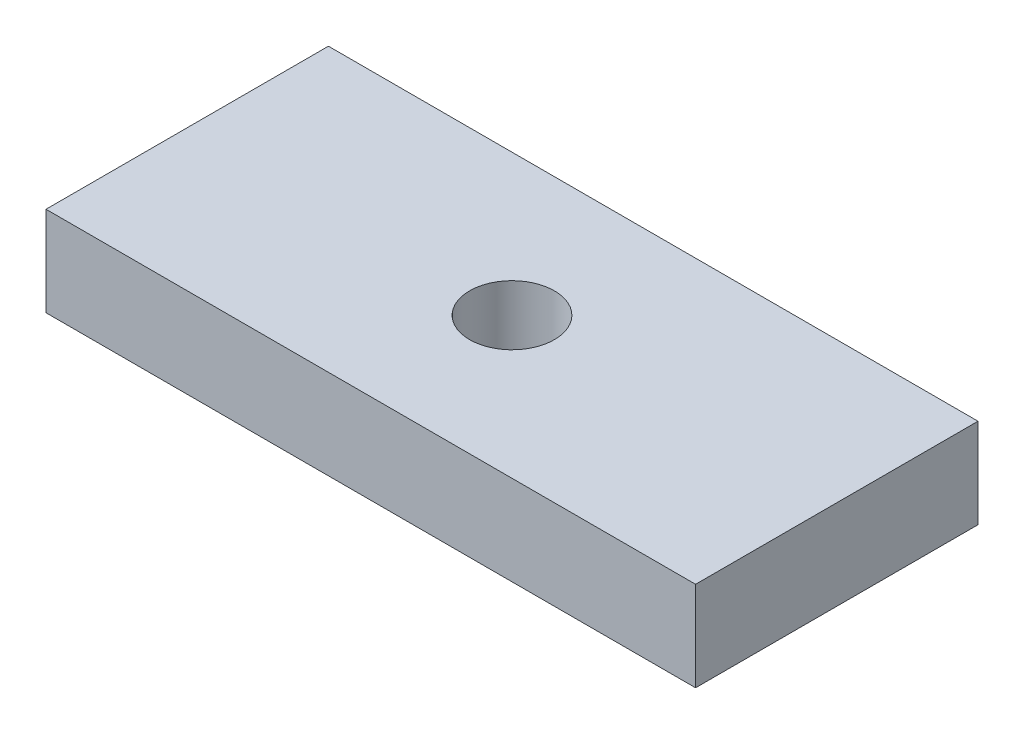
SolidWorks part; units mm, degrees
ref_plane "Front Plane" through (0, 0, 0) normal (0, 0, 1) x (1, 0, 0)
ref_plane "Top Plane" through (0, 0, 0) normal (0, 1, 0) x (1, 0, 0)
ref_plane "Right Plane" through (0, 0, 0) normal (1, 0, 0) x (0, 0, -1)
sketch "Sketch1" plane through (0, 0, 0) normal (0, 1, 0) x (1, 0, 0)
  line L1 (-23, 10) -> (23, 10)
  line L2 (-23, 10) -> (-23, -10)
  line L3 (-23, -10) -> (23, -10)
  line L4 (23, 10) -> (23, -10)
  line L5 (-23, 10) -> (23, -10) construction
  line L6 (-23, -10) -> (23, 10) construction
  circle A0 centre (0, 0) radius 3
  dimension "D1" = 6
  dimension "D2" = 20
  dimension "D3" = 46
extrude "Boss-Extrude1" add sketch "Sketch1" along normal blind 6.35
